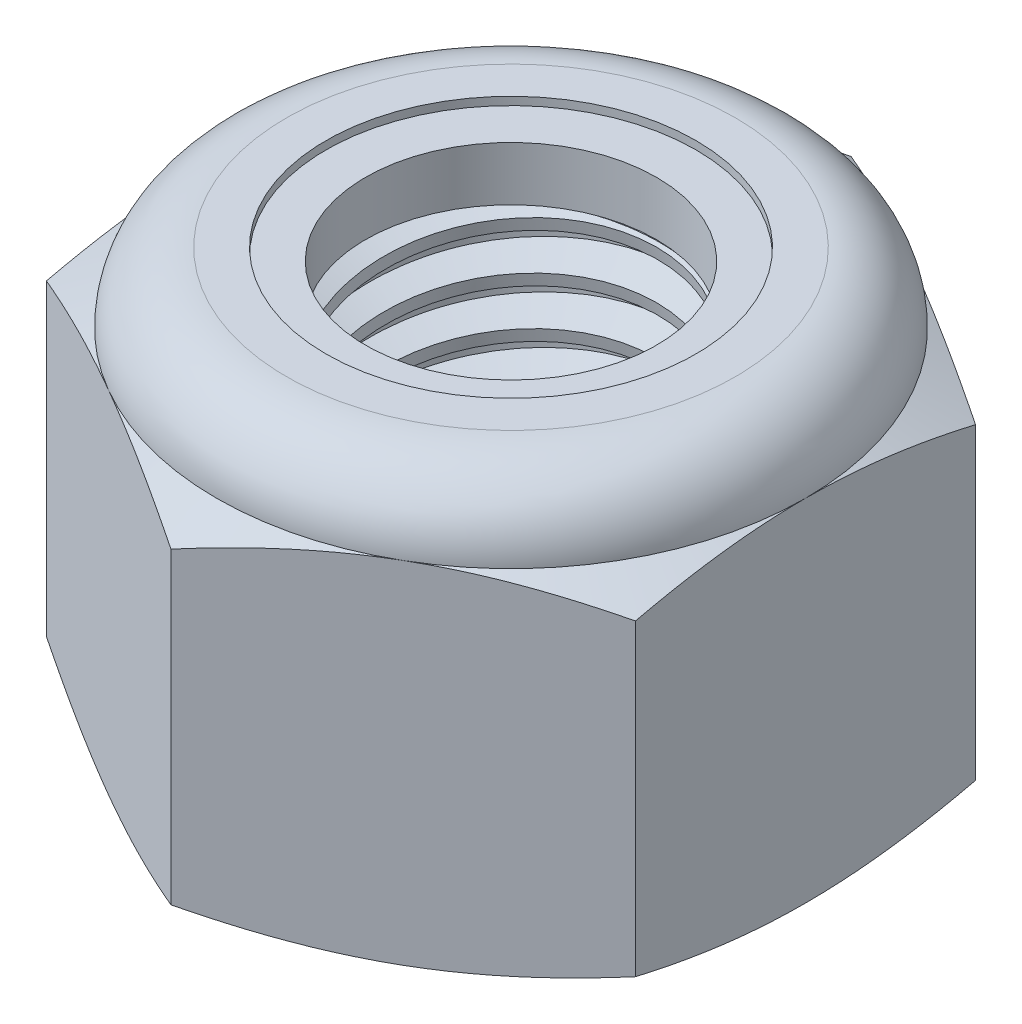
SolidWorks part; units mm, degrees
material "Chrome Stainless Steel"
ref_plane "Front" through (0, 0, 0) normal (0, 0, 1) x (1, 0, 0)
ref_plane "Top" through (0, 0, 0) normal (0, 1, 0) x (1, 0, 0)
ref_plane "Right" through (0, 0, 0) normal (1, 0, 0) x (0, 0, -1)
sketch "Sketch1" plane through (0, 0, 0) normal (0, 1, 0) x (1, 0, 0)
  line L1 (0, 6.4158) -> (-5.5563, 3.2079)
  line L2 (-5.5563, 3.2079) -> (-5.5563, -3.2079)
  line L3 (-5.5563, -3.2079) -> (0, -6.4158)
  line L4 (0, -6.4158) -> (5.5562, -3.2079)
  line L5 (5.5562, -3.2079) -> (5.5562, 3.2079)
  line L6 (5.5562, 3.2079) -> (0, 6.4158)
  circle A0 centre (0, 0) radius 5.5563 construction
  dimension "Hex Flats" = 11.1125
extrude "Extrude1" add sketch "Sketch1" along normal blind 7.9375
sketch "Sketch2" plane through (0, 0, 0) normal (1, 0, 0) x (0, 0, -1)
  line L0 (-3.175, 0) -> (-3.175, 7.9375) construction
  line L1 (0, 0) -> (3.175, 0)
  line L2 (0, 0) -> (0, 7.9375)
  line L3 (0, 7.9375) -> (3.175, 7.9375)
  line L4 (3.175, 0) -> (3.175, 7.9375)
  line L5 (-3.2079, 7.9375) -> (3.2079, 7.9375) construction
  line L7 (0, -3.175) -> (0, 0) construction
  dimension "Thread Dia" = 6.35
revolve "Revolve1" add sketch "Sketch2" angle 360 about L7
sketch "Sketch3" plane through (0, 0, 0) normal (1, 0, 0) x (0, 0, -1)
  line L0 (3.175, 7.9375) -> (-3.175, 7.9375) construction
  line L1 (-3.175, 7.9375) -> (-3.175, 7.0304) construction
  line L2 (-3.175, 7.0304) -> (3.175, 7.9375) construction
  line L3 (3.175, 7.9375) -> (3.191, 7.8252) construction
  line L4 (3.191, 7.8252) -> (3.3033, 7.0395)
  line L5 (3.3033, 7.0395) -> (2.7771, 7.2507)
  line L6 (2.7771, 7.2507) -> (2.7451, 7.4752)
  line L7 (2.7451, 7.4752) -> (3.191, 7.8252)
  line L8 (2.7611, 7.3629) -> (3.2472, 7.4324) construction
  line L9 (3.175, 7.9375) -> (3.175, 7.4221) construction
  line L10 (3.175, 7.4221) -> (-3.175, 6.5149) construction
  line L11 (-3.175, 6.5149) -> (-3.175, 7.0304) construction
  line L12 (-0.1384, 7.9375) -> (0.1384, 5.9995) construction
  line L13 (-3.175, 0) -> (-3.175, 7.9375) construction
  line L14 (0, 7.9375) -> (3.175, 7.9375) construction
  line L15 (3.175, 0) -> (3.175, 7.9375) construction
  point P13 (0, 6.9685)
  dimension "D1" = 0.1134
  dimension "D2" = 0.2268
  dimension "Thread Pitch" = 0.9071
  dimension "D4" = 60
  dimension "D5" = 0.9071
revolve "Cut-Revolve1" cut sketch "Sketch3" angle 360 about L12
pattern_linear "LPattern1" count 9 spacing 0.9071 along (0, -1, 0) count 2 spacing 0.9071 along (0, 1, 0) of "Cut-Revolve1"
sketch "Sketch4" plane through (0, 0, 0) normal (1, 0, 0) x (0, 0, -1)
  line L0 (0, 7.9375) -> (3.175, 7.9375)
  line L1 (3.175, 7.9375) -> (2.7451, 7.737)
  line L2 (2.7451, 7.737) -> (2.7451, 0.2005)
  line L3 (2.7451, 0.2005) -> (3.175, 0)
  line L4 (3.175, 0) -> (0, 0)
  line L5 (0, 0) -> (0, 7.9375)
  line L6 (3.175, 0) -> (3.175, 7.9375) construction
  line L7 (0, 7.9375) -> (3.175, 7.9375) construction
  line L8 (0, 0) -> (3.175, 0) construction
  line L9 (0, 0) -> (0, 7.9375) construction
  line L10 (0, 7.9375) -> (0, 8.4119) construction
  dimension "D1" = 25
revolve "Cut-Revolve2" cut sketch "Sketch4" angle 360 about L10
combine bodies "Combine1" operation type subtract main body 112 bodies to subtract 111
sketch "Sketch5" plane through (0, 0, 0) normal (1, 0, 0) x (0, 0, -1)
  line L0 (0, 0) -> (5.5563, 0)
  line L1 (5.5563, 0) -> (6.4158, 0.4008)
  line L2 (6.4158, 0.4008) -> (6.4158, 6.2138)
  line L3 (6.4158, 6.2138) -> (5.5563, 6.6146)
  line L4 (4.2333, 7.9375) -> (4.2333, 9.2075)
  line L5 (4.2333, 9.2075) -> (7.6858, 9.2075)
  line L6 (7.6858, 9.2075) -> (7.6858, -1.27)
  line L7 (7.6858, -1.27) -> (0, -1.27)
  line L8 (0, -1.27) -> (0, 0)
  line L9 (5.5563, 6.6146) -> (5.5563, 0) construction
  line L10 (0, 0) -> (3.175, 0) construction
  line L13 (6.4158, 3.3073) -> (7.6858, 3.3073) construction
  line L14 (6.4158, 7.9375) -> (6.4158, 0) construction
  line L15 (0, 0) -> (0, 9.2075) construction
  line L20 (0, 9.2075) -> (4.2333, 9.2075) construction
  line L22 (0, 7.9375) -> (3.175, 7.9375) construction
  arc A0 (5.5563, 6.6146) -> (4.2333, 7.9375) centre (4.2333, 6.6146) ccw
  dimension "D1" = 25
  dimension "D2" = 1.27
  dimension "D3" = 7.9375
  dimension "D4" = 1.3229
revolve "Cut-Revolve3" cut sketch "Sketch5" angle 360 about L15
sketch "Sketch6" plane through (0, 0, 0) normal (1, 0, 0) x (0, 0, -1)
  line L0 (0, 6.6146) -> (5.4039, 6.6146)
  line L1 (4.2333, 7.7851) -> (3.4892, 7.7851)
  line L2 (0, 9.2075) -> (0, 6.6146)
  line L3 (3.4892, 9.2075) -> (0, 9.2075)
  line L4 (0, 9.2075) -> (4.2333, 9.2075) construction
  line L5 (0, 0) -> (0, 9.2075) construction
  line L6 (0, 9.2075) -> (0, 44.323) construction
  line L7 (3.4892, 7.7851) -> (3.4892, 9.2075)
  line L8 (4.2333, 7.9375) -> (4.2333, 7.7851) construction
  line L9 (3.4892, 7.7851) -> (2.7451, 7.7851) construction
  line L10 (2.7451, 7.7851) -> (2.7451, 7.737) construction
  arc A0 (5.4039, 6.6146) -> (4.2333, 7.7851) centre (4.2333, 6.6146) ccw
  arc A1 (5.5563, 6.6146) -> (4.2333, 7.9375) centre (4.2333, 6.6146) ccw construction
  dimension "D1" = 0.1524
revolve "Cut-Revolve4" cut sketch "Sketch6" angle 360 about L6
sketch "Sketch7" plane through (0, 0, 0) normal (1, 0, 0) x (0, 0, -1)
  line L0 (2.7451, 6.6908) -> (5.325, 6.6908)
  line L1 (4.2333, 7.7089) -> (2.7451, 7.7089)
  line L2 (2.7451, 7.7089) -> (2.7451, 6.6908)
  line L3 (2.7451, 6.6908) -> (0, 6.6908) construction
  line L4 (0, 6.6908) -> (0, 7.7089) construction
  line L5 (0, 7.7089) -> (2.7451, 7.7089) construction
  line L6 (2.7451, 6.6908) -> (2.7451, 6.6146) construction
  line L7 (0, 6.6146) -> (5.4039, 6.6146) construction
  line L8 (4.2333, 7.7089) -> (4.2333, 7.7851) construction
  arc A0 (5.325, 6.6908) -> (4.2333, 7.7089) centre (4.2333, 6.6146) ccw
  arc A2 (5.4039, 6.6146) -> (4.2333, 7.7851) centre (4.2333, 6.6146) ccw construction
  dimension "D1" = 0.0762
revolve "Revolve2" add sketch "Sketch7" angle 360 about L4
equation "\"D1@Sketch3\"=\"Thread Pitch@Sketch3\"/8"
equation "\"D2@Sketch3\"=\"Thread Pitch@Sketch3\"/4"
equation "\"D5@Sketch3\"=\"Thread Pitch@Sketch3\""
equation "\"D4@LPattern1\"=\"Thread Pitch@Sketch3\""
equation "\"D3@LPattern1\"=\"Thread Pitch@Sketch3\""
equation "\"D1@LPattern1\"=\"Height@Extrude1\"/\"Thread Pitch@Sketch3\""
equation "\"D4@Sketch5\"=\"Height@Extrude1\"/6"
